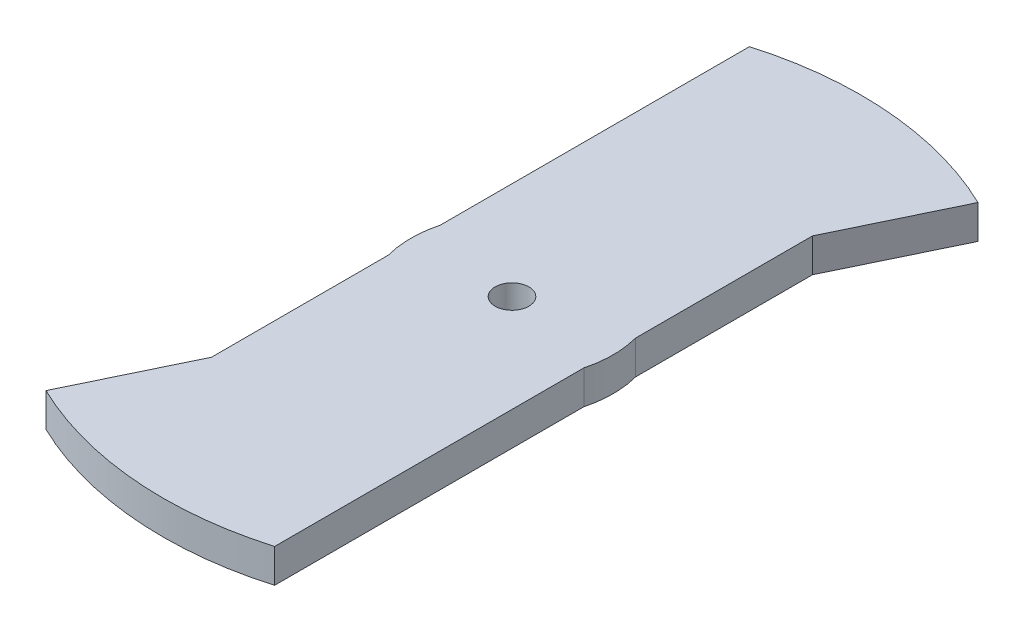
SolidWorks part; units mm, degrees
material "AISI 316 Stainless Steel Sheet (SS)"
ref_plane "Front Plane" through (0, 0, 0) normal (0, 0, 1) x (1, 0, 0)
ref_plane "Top Plane" through (0, 0, 0) normal (0, 1, 0) x (1, 0, 0)
ref_plane "Right Plane" through (0, 0, 0) normal (1, 0, 0) x (0, 0, -1)
sketch "Sketch1" plane through (0, 0, 0) normal (0, 1, 0) x (1, 0, 0)
  line L0 (0, 19.05) -> (0, 65.786) construction
  line L1 (-18.415, 63.156) -> (-18.415, 4.8775)
  line L2 (18.415, 4.8775) -> (18.415, 38.2122)
  line L3 (18.415, 38.2122) -> (28.5598, 59.2633)
  line L4 (18.415, -63.156) -> (18.415, -4.8775)
  line L5 (-18.415, -38.2122) -> (-28.5598, -59.2633)
  line L6 (-18.415, -4.8775) -> (-18.415, -38.2122)
  circle A0 centre (0, 0) radius 3.175
  circle A1 centre (0, 0) radius 19.05 construction
  circle A2 centre (0, 0) radius 65.786 construction
  arc A3 (-18.415, 63.156) -> (28.5598, 59.2633) centre (0, 0) cw
  circle A4 centre (0, 0) radius 42.418 construction
  arc A5 (18.415, -63.156) -> (-28.5598, -59.2633) centre (0, 0) cw
  arc A6 (-18.415, 4.8775) -> (-18.415, -4.8775) centre (0, 0) ccw
  arc A7 (18.415, 4.8775) -> (18.415, -4.8775) centre (0, 0) cw
  point P9 (18.415, 4.8775)
  point P15 (0, 42.418)
  point P23 (0, 0)
  dimension "D1" = 6.35
  dimension "D2" = 38.1
  dimension "D3" = 131.572
  dimension "D4" = 36.83
  dimension "D6" = 2
extrude "Boss-Extrude1" add sketch "Sketch1" along normal blind 6.35 contours A7 L2 L3 A3 L1 A6 L6 L5 A5 L4 A0
